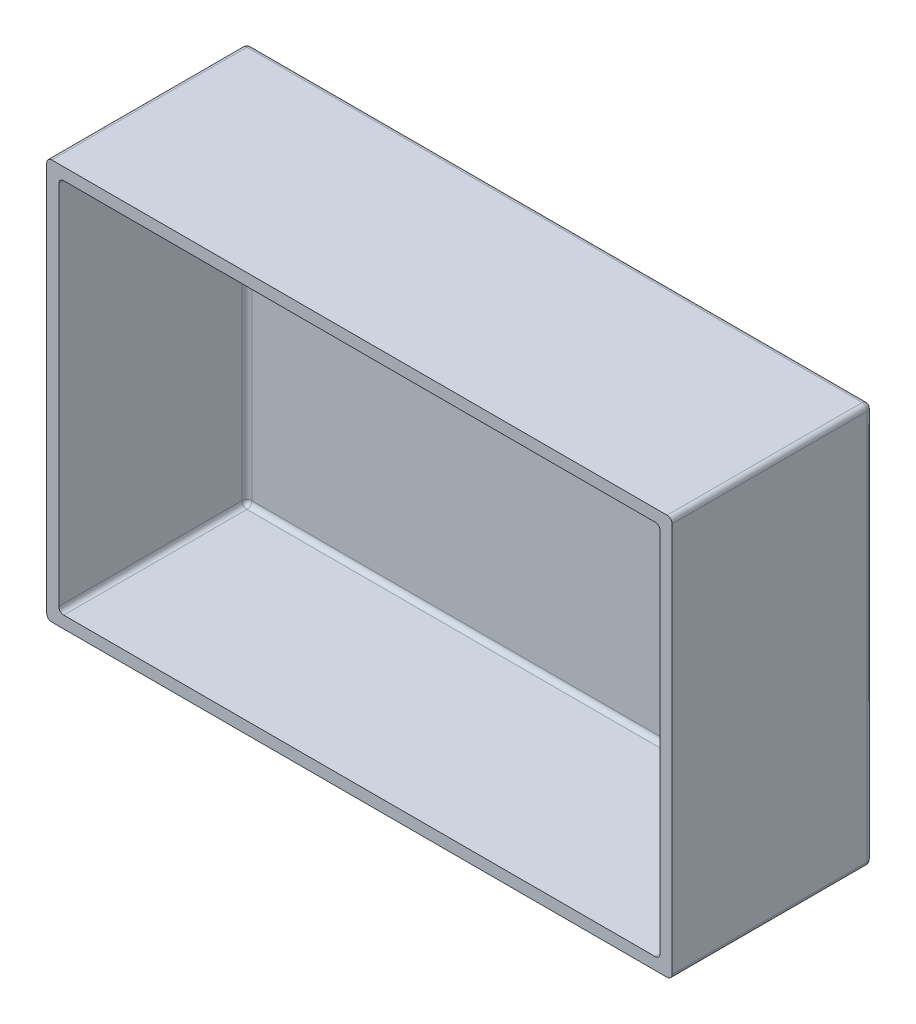
SolidWorks part; units mm, degrees
material "Резина"
ref_plane "Спереди" through (0, 0, 0) normal (0, 0, 1) x (1, 0, 0)
ref_plane "Сверху" through (0, 0, 0) normal (0, 1, 0) x (1, 0, 0)
ref_plane "Справа" through (0, 0, 0) normal (1, 0, 0) x (0, 0, -1)
sketch "Эскиз1" plane through (0, 0, 0) normal (0, 0, 1) x (1, 0, 0)
  line L1 (-62.5, 40) -> (62.5, 40)
  line L2 (-62.5, 40) -> (-62.5, -40)
  line L3 (-62.5, -40) -> (62.5, -40)
  line L4 (62.5, 40) -> (62.5, -40)
  line L5 (-62.5, 40) -> (62.5, -40) construction
  line L6 (-62.5, -40) -> (62.5, 40) construction
  point P0 (0, 0)
  dimension "D1" = 125
  dimension "D2" = 80
extrude "Бобышка-Вытянуть1" add sketch "Эскиз1" along normal blind 40
sketch "Эскиз2" plane through (0, 0, 40) normal (0, 0, 1) x (1, 0, 0)
  line L0 (62.5, 40) -> (-62.5, 40) construction
  line L1 (-60.1, 37.6) -> (60.1, 37.6)
  line L2 (-60.1, 37.6) -> (-60.1, -37.6)
  line L3 (-60.1, -37.6) -> (60.1, -37.6)
  line L4 (60.1, 37.6) -> (60.1, -37.6)
  line L5 (-60.1, 37.6) -> (60.1, -37.6) construction
  line L6 (-60.1, -37.6) -> (60.1, 37.6) construction
  line L7 (62.5, -40) -> (62.5, 40) construction
  point P0 (0, 0)
  dimension "D1" = 2.4
  dimension "D2" = 2.4
extrude "Вырез-Вытянуть1" cut sketch "Эскиз2" against normal blind 37.6
fillet "Скругление1" radius 1 8 edges at (62.5, -40, 20) (62.5, 40, 20) (62.5, 0, 0) (0, 40, 0) (-62.5, 40, 20) (-62.5, -40, 20) (0, -40, 0) (-62.5, 0, 0)
fillet "Скругление2" radius 1 8 edges at (60.1, 37.6, 21.2) (60.1, 0, 2.4) (60.1, -37.6, 21.2) (0, 37.6, 2.4) (-60.1, 37.6, 21.2) (0, -37.6, 2.4) (-60.1, -37.6, 21.2) (-60.1, 0, 2.4)
sketch "Эскиз3" plane through (0, 0, 0) normal (0, 0, -1) x (-1, 0, 0)
  line L0 (-61.5, 5) -> (59.5, 5) construction
  line L4 (-61.5, 39) -> (-61.5, -39) construction
  text T0 "Для\r\nЗСУ" font "Times New Roman" height 20
  dimension "D1" = 5
extrude "Вырез-Вытянуть2" [suppressed] cut sketch "Эскиз3" against normal blind 0.5
sketch "Эскиз4" plane through (62.5, 0, 0) normal (1, 0, 0) x (0, 0, -1)
  line L0 (0, 0) -> (-20.5, 0) construction
  line L1 (-20.5, -4) -> (-20.5, 4)
  line L2 (-20.5, 4) -> (-21.5858, 4)
  line L3 (-23.5, 2.0858) -> (-23.5, -2.0858)
  line L4 (-15.75, 0) -> (-20.5, 0) construction
  line L5 (-13, 6.5) -> (-18.5, 6.5)
  line L6 (-13, 6.5) -> (-13, -6.5)
  line L7 (-13, -6.5) -> (-18.5, -6.5)
  line L8 (-18.5, 6.5) -> (-18.5, -6.5)
  line L9 (-13, 6.5) -> (-18.5, -6.5) construction
  line L10 (-13, -6.5) -> (-18.5, 6.5) construction
  line L11 (-22.2929, 3.7071) -> (-23.2071, 2.7929)
  line L12 (-22.2929, -3.7071) -> (-23.2071, -2.7929)
  line L13 (-20.5, -4) -> (-21.5858, -4)
  arc A0 (-22.2929, -3.7071) -> (-21.5858, -4) centre (-21.5858, -3) ccw
  arc A1 (-23.2071, -2.7929) -> (-23.5, -2.0858) centre (-22.5, -2.0858) cw
  arc A2 (-23.2071, 2.7929) -> (-23.5, 2.0858) centre (-22.5, 2.0858) ccw
  arc A3 (-22.2929, 3.7071) -> (-21.5858, 4) centre (-21.5858, 3) cw
  point P5 (-15.75, 0)
  point P15 (-23.5, 0)
  point P18 (-22, -4)
  point P21 (-23.5, -2.5)
  point P24 (-23.5, 2.5)
  point P27 (-22, 4)
  dimension "D9" = 1
  dimension "D1" = 13
  dimension "D2" = 5.5
  dimension "D3" = 13
  dimension "D4" = 2
  dimension "D5" = 3
  dimension "D6" = 8
  dimension "D7" = 1.5
  dimension "D8" = 1.5
extrude "Вырез-Вытянуть3" [suppressed] cut sketch "Эскиз4" against normal blind 5
sketch "Эскиз5" plane through (60.1, 0, 0) normal (-1, 0, 0) x (0, 0, 1)
  line L0 (11.4, 0) -> (29.8169, 0) construction
  line L1 (11.4, 0) -> (11.4, -8.5)
  line L2 (11.4, -8.5) -> (13, -8.5)
  line L3 (13, -8.5) -> (13, 8.5)
  line L4 (11.4, 0) -> (11.4, 8.5)
  line L5 (11.4, 8.5) -> (13, 8.5)
  line L13 (0, -39) -> (0, 39) construction
  line L15 (11.4, -8.5) -> (21.4, -8.5)
  line L16 (11.4, -8.5) -> (11.4, -10.1)
  line L17 (11.4, -10.1) -> (21.4, -10.1)
  line L18 (21.4, -8.5) -> (21.4, -10.1)
  line L19 (11.4, -8.5) -> (21.4, -10.1) construction
  line L20 (11.4, -10.1) -> (21.4, -8.5) construction
  point P8 (16.4, -9.3)
  dimension "D1" = 1.6
  dimension "D2" = 17
  dimension "D3" = 8.5
  dimension "D4" = 13
  dimension "D5" = 17
  dimension "D6" = 1.6
  dimension "D7" = 10
  dimension "D8" = 11.4
extrude "Бобышка-Вытянуть2" [suppressed] add sketch "Эскиз5" along normal blind 20
sketch "Эскиз6" [suppressed] plane through (0, 0, 13) normal (0, 0, 1) x (1, 0, 0)
  line L0 (40.1, 0) -> (43.5026, 0) construction
  line L1 (40.1, -8.5) -> (40.1, 8.5) construction
  line L2 (40.1, 8.5) -> (60.1, 8.5) construction
  line L3 (43.6526, -1.5) -> (43.3526, -1.5)
  line L4 (43.9026, -1.25) -> (43.9026, 1.25)
  line L5 (43.6526, 1.5) -> (43.3526, 1.5)
  line L6 (43.1026, -1.25) -> (43.1026, 1.25)
  line L7 (43.9026, -1.5) -> (43.1026, 1.5) construction
  line L8 (43.9026, 1.5) -> (43.1026, -1.5) construction
  line L9 (45.9832, 6.5) -> (43.9832, 6.5)
  line L10 (46.2332, 6.75) -> (46.2332, 7.05)
  line L11 (45.9832, 7.3) -> (43.9832, 7.3)
  line L12 (43.7332, 6.75) -> (43.7332, 7.05)
  line L13 (46.2332, 6.5) -> (43.7332, 7.3) construction
  line L14 (46.2332, 7.3) -> (43.7332, 6.5) construction
  arc A0 (43.9026, 1.25) -> (43.6526, 1.5) centre (43.6526, 1.25) ccw
  arc A1 (43.1026, 1.25) -> (43.3526, 1.5) centre (43.3526, 1.25) cw
  arc A2 (43.3526, -1.5) -> (43.1026, -1.25) centre (43.3526, -1.25) cw
  arc A3 (43.9026, -1.25) -> (43.6526, -1.5) centre (43.6526, -1.25) cw
  arc A4 (43.7332, 7.05) -> (43.9832, 7.3) centre (43.9832, 7.05) cw
  arc A5 (43.9832, 6.5) -> (43.7332, 6.75) centre (43.9832, 6.75) cw
  arc A6 (46.2332, 7.05) -> (45.9832, 7.3) centre (45.9832, 7.05) ccw
  arc A7 (46.2332, 6.75) -> (45.9832, 6.5) centre (45.9832, 6.75) cw
  point P8 (44.9832, 6.9)
  point P15 (44.9832, 7.3)
  dimension "D7" = 0.25
  dimension "D8" = 0.25
  dimension "D1" = 0.8
  dimension "D2" = 3
  dimension "D3" = 8.5
  dimension "D4" = 0.8
  dimension "D5" = 2.5
  dimension "D6" = 1.2
extrude "Бобышка-Вытянуть3" [suppressed] add sketch "Эскиз6" along normal blind 8
